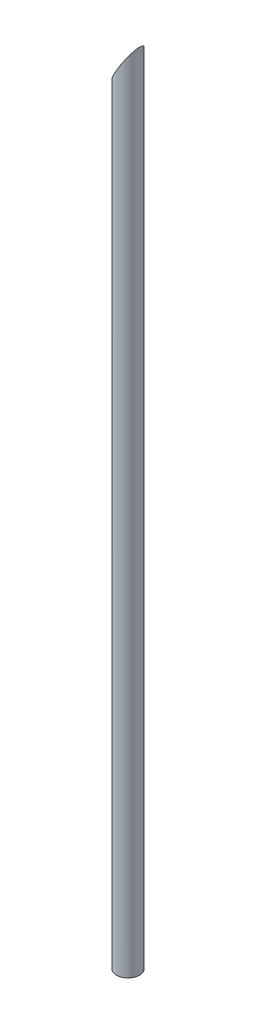
SolidWorks part; units mm, degrees
material "6061 Alloy"
ref_plane "Front Plane" through (0, 0, 0) normal (0, 0, 1) x (1, 0, 0)
ref_plane "Top Plane" through (0, 0, 0) normal (0, 1, 0) x (1, 0, 0)
ref_plane "Right Plane" through (0, 0, 0) normal (1, 0, 0) x (0, 0, -1)
sketch "Sketch1" plane through (0, 0, 0) normal (0, 1, 0) x (1, 0, 0)
  circle A0 centre (0, 0) radius 16.7005
  circle A1 centre (0, 0) radius 13.3223
  dimension "D1" = 33.401
  dimension "D2" = 26.6446
extrude "Boss-Extrude1" add sketch "Sketch1" along normal blind 1168.4
sketch "Sketch2" plane through (0, 0, 0) normal (0, 0, 1) x (1, 0, 0)
  line L0 (-16.7005, 1168.4) -> (-16.7005, 0) construction
  line L1 (16.7005, 0) -> (16.7005, 1168.4) construction
  line L2 (16.7005, 1168.4) -> (-16.7005, 1168.4) construction
  line L3 (-16.7005, 1168.4) -> (-16.7005, 0)
  line L4 (16.7005, 0) -> (16.7005, 1168.4)
  line L5 (16.7005, 1168.4) -> (-16.7005, 1168.4)
  line L6 (16.7005, 1168.4) -> (-16.7005, 1110.5478)
  dimension "D1" = 60
extrude "Cut-Extrude1" cut sketch "Sketch2" against normal through all both and the other way through all contours L6 L5 L3
sketch "Sketch3" plane through (-493.4067, 284.8685, 0) normal (-0.866, 0.5, 0) x (0, 0, 1)
  ellipse E0 centre (0, 986.8133) end of major axis (0, 953.4123) minor radius 16.7005 construction
  point P0 (0, 1020.2143)
  point P1 (0, 953.4123)
ref_point "Point1"
ref_point "Point2"
